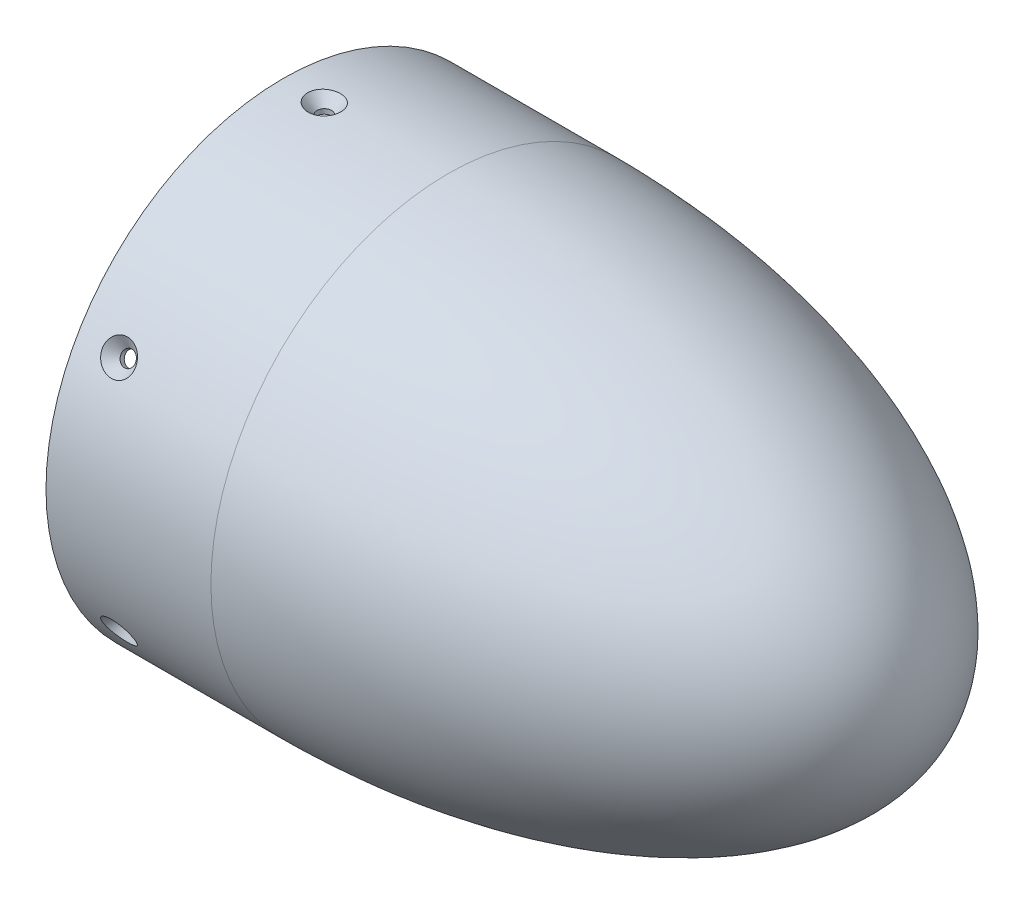
SolidWorks part; units mm, degrees
material "6061 Alloy"
ref_plane "Front Plane" through (0, 0, 0) normal (0, 0, 1) x (1, 0, 0)
ref_plane "Top Plane" through (0, 0, 0) normal (0, 1, 0) x (1, 0, 0)
ref_plane "Right Plane" through (0, 0, 0) normal (1, 0, 0) x (0, 0, -1)
sketch "Sketch1" plane through (0, 0, 0) normal (0, 0, 1) x (1, 0, 0)
  line L0 (0, -63.5) -> (0, -73.025)
  line L1 (134.3323, 0) -> (146.05, 0)
  line L2 (120.65, -29.311) -> (124.9467, -37.8118) construction
  line L3 (120.65, -29.311) -> (109.0428, -35.1778) construction
  line L4 (134.3323, 0) -> (127, -12.7)
  line L5 (127, -12.7) -> (120.65, -12.7)
  line L6 (120.65, -12.7) -> (120.65, -29.311)
  line L7 (50.8, -58.1987) -> (50.8, -50.8)
  line L8 (50.8, -50.8) -> (76.2, -50.8)
  line L9 (76.2, -50.8) -> (76.2, -38.1)
  line L10 (76.2, -38.1) -> (101.6, -38.1)
  line L11 (101.6, -38.1) -> (101.6, -29.311)
  line L12 (120.65, -29.311) -> (101.6, -29.311)
  ellipse E0 centre (0, 0) end of major axis (146.05, 0) minor radius 73.025 (146.05, 0) -> (0, -73.025) cw
  ellipse E1 centre (0, 0) end of major axis (127, 0) minor radius 63.5 (50.8, -58.1987) -> (0, -63.5) cw
  dimension "D1" = 73.025
  dimension "D2" = 146.05
  dimension "D3" = 9.525
  dimension "D4" = 60
  dimension "D5" = 127
  dimension "D6" = 12.7
  dimension "D7" = 120.65
  dimension "D8" = 50.8
  dimension "D9" = 127
  dimension "D10" = 76.2
  dimension "D11" = 101.6
revolve "Revolve1" add sketch "Sketch1" angle 360 about L1
sketch "Sketch2" plane through (0, 0, 0) normal (-1, 0, 0) x (0, 0, 1)
  circle A0 centre (0, 0) radius 63.5
  circle A1 centre (0, 0) radius 73.025
  circle A2 centre (0, 0) radius 73.025 construction
  circle A4 centre (0, 0) radius 63.5 construction
extrude "Boss-Extrude1" add sketch "Sketch2" along normal blind 50.8
sketch "Sketch4" plane through (-50.8, 0, 0) normal (-1, 0, 0) x (0, 0, 1)
  circle A0 centre (0, 0) radius 63.5
  circle A1 centre (0, 0) radius 68.2625
  circle A3 centre (0, 0) radius 63.5 construction
  dimension "D1" = 136.525
extrude "Cut-Extrude2" cut sketch "Sketch4" against normal blind 25.4
ref_plane "Plane1" through (0, 73.025, 0) normal (0, 1, 0) x (1, 0, 0)
hole_wizard "CSK for #8 Flat Head Socket Cap Screw1" positions "Sketch6" profile "Sketch7" countersink size "#8" standard "ANSI Inch"
sketch "Sketch6" plane through (0, 73.025, 0) normal (0, 1, 0) x (1, 0, 0)
  line L0 (-50.8, 73.025) -> (-50.8, -73.025) construction
  point P0 (-38.1, 0)
  dimension "D1" = 12.7
sketch "Sketch7" plane through (-38.1, 73.025, 0) normal (1, 0, 0) x (0, 0, 1)
  line L0 (0, 0) -> (0, 26.7507)
  line L1 (0, 26.7507) -> (2.2479, 25.4)
  line L2 (2.2479, 25.4) -> (2.2479, 3.294)
  line L3 (2.2479, 3.294) -> (5.1113, 0)
  line L5 (5.1113, 0) -> (0, 0)
  line L6 (-2.2479, 3.294) -> (-5.1113, 0) construction
  line L10 (0, 26.7507) -> (-2.2479, 25.4) construction
  line L11 (0, -6.35) -> (0, 107.95) construction
  dimension "Hole Dia." = 4.4958
  dimension "Hole Depth" = 25.4
  dimension "Near C'Sink Dia." = 10.2226
  dimension "Near C'Sink Angle" = 82
  dimension "Drill Angle" = 118
pattern_circular "CirPattern1" count 6 over 360 about axis through (-25.4, 0, 0) along (-1, 0, 0) of "CSK for #8 Flat Head Socket Cap Screw1"
chamfer "Chamfer1" distance 1.27 angle 45 1 edges at (-50.8, -68.2625, 0)
